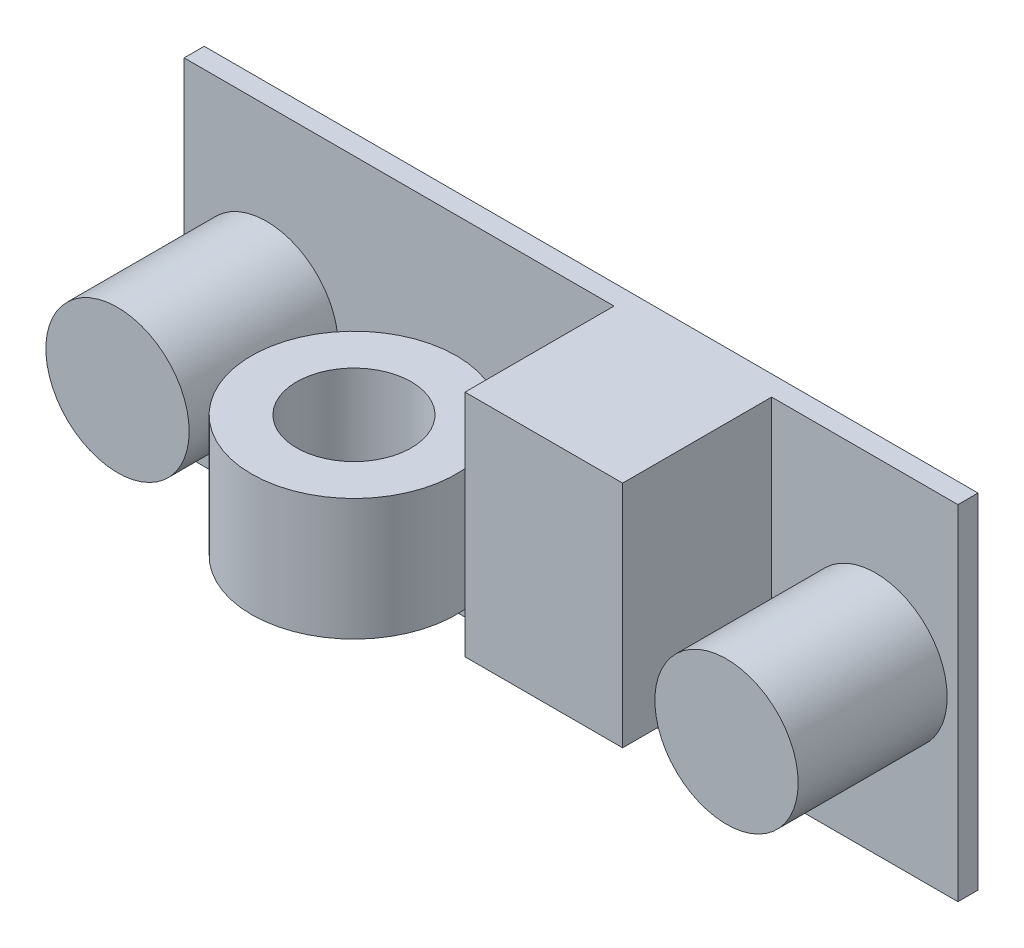
SolidWorks part; units mm, degrees
ref_plane "Plano frontal" through (0, 0, 0) normal (0, 0, 1) x (1, 0, 0)
ref_plane "Plano superior" through (0, 0, 0) normal (0, 1, 0) x (1, 0, 0)
ref_plane "Plano direito" through (0, 0, 0) normal (1, 0, 0) x (0, 0, -1)
sketch "Esboço1" plane through (0, 0, 0) normal (0, 0, 1) x (1, 0, 0)
  line L1 (-27, 12) -> (27, 12)
  line L2 (-27, 12) -> (-27, -12)
  line L3 (-27, -12) -> (27, -12)
  line L4 (27, 12) -> (27, -12)
  line L5 (-27, 12) -> (27, -12) construction
  line L6 (-27, -12) -> (27, 12) construction
  point P0 (0, 0)
  dimension "D1" = 54
  dimension "D2" = 24
extrude "Ressalto-extrusão1" add sketch "Esboço1" along normal blind 1.4
sketch "Esboço2" plane through (0, 0, 1.4) normal (0, 0, 1) x (1, 0, 0)
  line L0 (0, 0) -> (0, 13.1098) construction
  line L1 (27, -12) -> (27, 12) construction
  line L2 (3, 12) -> (14, 12)
  line L3 (3, 12) -> (3, -4)
  line L4 (3, -4) -> (14, -4)
  line L5 (14, 12) -> (14, -4)
  line L6 (3, 12) -> (14, -4) construction
  line L7 (3, -4) -> (14, 12) construction
  line L8 (27, 12) -> (-27, 12) construction
  circle A0 centre (21.25, 0) radius 5
  circle A1 centre (-21.25, 0) radius 5
  point P9 (8.5, 4)
  point P16 (5.9506, 12)
  dimension "D1" = 10
  dimension "D2" = 42.5
  dimension "D3" = 13
  dimension "D4" = 16
  dimension "D5" = 11
extrude "Ressalto-extrusão2" add sketch "Esboço2" along normal blind 10.4
sketch "Esboço4" plane through (0, 0, 0) normal (0, 1, 0) x (1, 0, 0)
  line L0 (-27, -1.4) -> (27, -1.4) construction
  line L1 (-27, -1.4) -> (-27, 0) construction
  circle A0 centre (-8, -8.55) radius 7.15
  circle A1 centre (-8, -8.55) radius 4
  dimension "D1" = 14.3
  dimension "D2" = 8
  dimension "D3" = 19
extrude "Ressalto-extrusão3" add sketch "Esboço4" along normal offset from surface 8.5 and the other way offset from surface (5 mm away) 7 separate body up to face at (4.25, 12, 3.65) other way up to face at (0, -12, 0.7)
